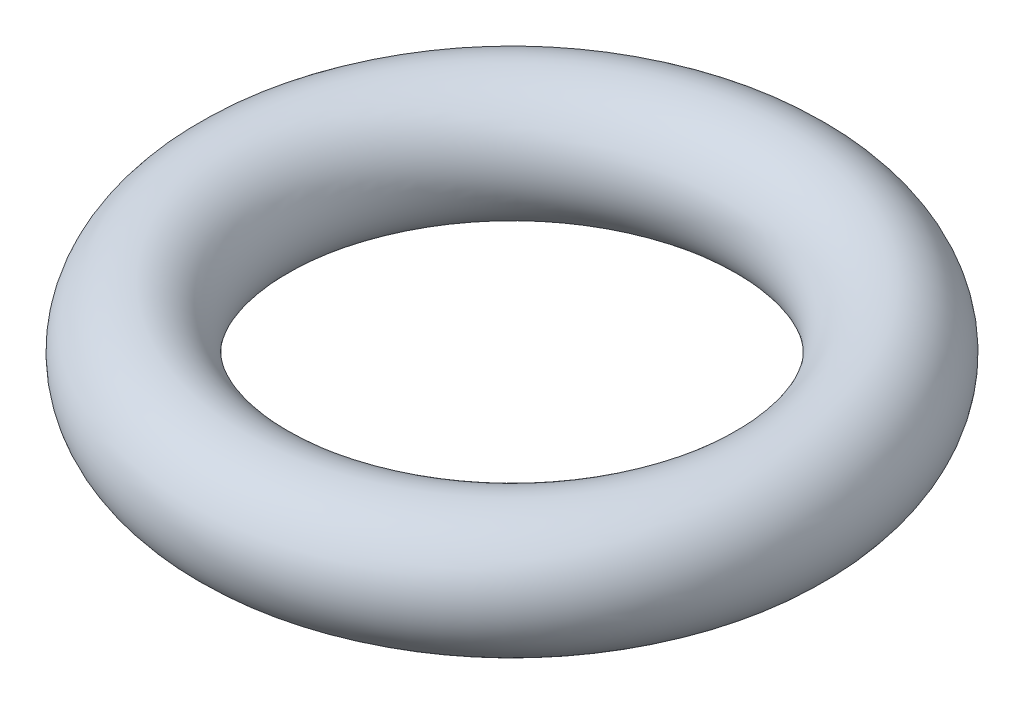
SolidWorks part; units mm, degrees
ref_plane "Спереди" through (0, 0, 0) normal (0, 0, 1) x (1, 0, 0)
ref_plane "Сверху" through (0, 0, 0) normal (0, 1, 0) x (1, 0, 0)
ref_plane "Справа" through (0, 0, 0) normal (1, 0, 0) x (0, 0, -1)
sketch "Эскиз1" plane through (0, 0, 0) normal (0, 0, 1) x (1, 0, 0)
  line L0 (0, 0) -> (0, 18.1388) construction
  circle A0 centre (6.5, 0) radius 1.5
  point P5 (0, 0)
  point P6 (0, 41.0124)
  point P7 (0, 18.1388)
  dimension "D1" = 3
  dimension "D2" = 10
revolve "Повернуть1" add sketch "Эскиз1" angle 360 about L0
equation "\"d1\"= 10.00мм"
equation "\"d2\"= 3.00мм"
equation "\"D1@Эскиз1\"=\"d2\""
equation "\"D2@Эскиз1\"=\"d1\""
